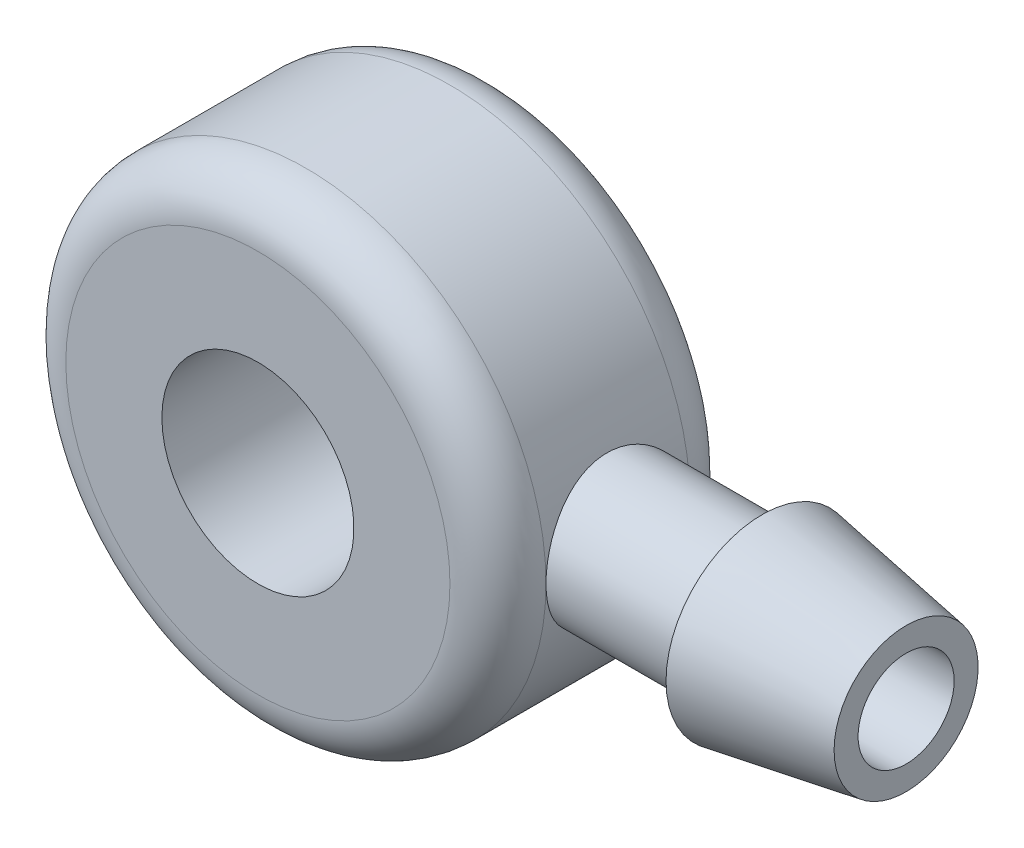
SolidWorks part; units mm, degrees
material "ABS"
ref_plane "Front" through (0, 0, 0) normal (0, 0, 1) x (1, 0, 0)
ref_plane "Top" through (0, 0, 0) normal (0, 1, 0) x (1, 0, 0)
ref_plane "Right" through (0, 0, 0) normal (1, 0, 0) x (0, 0, -1)
sketch "Sketch1" plane through (0, 0, 0) normal (0, 0, 1) x (1, 0, 0)
  circle A0 centre (0, 0) radius 5
extrude "Boss-Extrude1" add sketch "Sketch1" along normal blind 5
fillet "Fillet1" radius 1 2 edges at (5, 0, 0) (5, 0, 5)
sketch "Sketch2" plane through (0, 0, 0) normal (0, 0, -1) x (-1, 0, 0)
  circle A0 centre (0, 0) radius 2
extrude "Cut-Extrude1" cut sketch "Sketch2" against normal blind 5
ref_plane "Plane1" through (0, 0, 0) normal (0, 1, 0) x (1, 0, 0)
sketch "Sketch3" plane through (0, 0, 0) normal (0, 1, 0) x (1, 0, 0)
  line L0 (5, -2.5) -> (11, -2.5) construction
  line L1 (5, -4) -> (5, -1) construction
  line L2 (4.0945, -1) -> (8, -1)
  line L3 (8, -1) -> (8, -0.5)
  line L4 (8, -0.5) -> (11, -1)
  line L5 (11, -1) -> (11, -2.5)
  line L6 (11, -2.5) -> (4.0945, -2.5)
  line L7 (4.0945, -2.5) -> (4.0945, -1)
  dimension "D1" = 1.5
  dimension "D2" = 3
revolve "Revolve1" add sketch "Sketch3" angle 360 about L0
sketch "Sketch4" plane through (11, 0, 0) normal (1, 0, 0) x (0, 0, -1)
  circle A0 centre (-2.5, 0) radius 1
extrude "Cut-Extrude2" cut sketch "Sketch4" against normal blind 10
